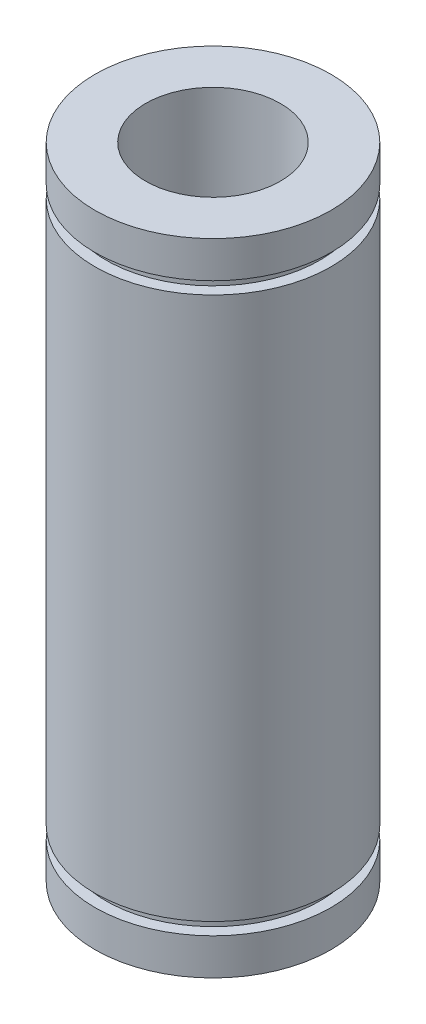
SolidWorks part; units mm, degrees
material "Plain Carbon Steel"
ref_plane "Front Plane" through (0, 0, 0) normal (0, 0, 1) x (1, 0, 0)
ref_plane "Top Plane" through (0, 0, 0) normal (0, 1, 0) x (1, 0, 0)
ref_plane "Right Plane" through (0, 0, 0) normal (1, 0, 0) x (0, 0, -1)
sketch "Sketch1" plane through (0, 0, 0) normal (0, 0, 1) x (1, 0, 0)
  line L0 (6, -16.5) -> (6, 12)
  line L1 (6, 12) -> (10.5, 12)
  line L2 (10.5, 12) -> (10.5, 8.75)
  line L3 (10.5, 8.75) -> (9.5, 8.75)
  line L4 (9.5, 8.75) -> (9.5, 7.65)
  line L8 (9.5, 7.65) -> (10.5, 7.65)
  line L9 (10.5, 7.65) -> (10.5, -16.5)
  line L10 (6, -16.5) -> (10.5, -16.5)
  line L11 (0, 0) -> (0, 12) construction
  dimension "D1" = 28.5
  dimension "D2" = 6
  dimension "D3" = 4.5
  dimension "D4" = 3.25
  dimension "D5" = 1.1
  dimension "D6" = 1
revolve "Revolve1" add sketch "Sketch1" angle 360 about L11
mirror "Mirror1" about plane through (6, -16.5, 0) normal (0, -1, 0) of "Revolve1"
